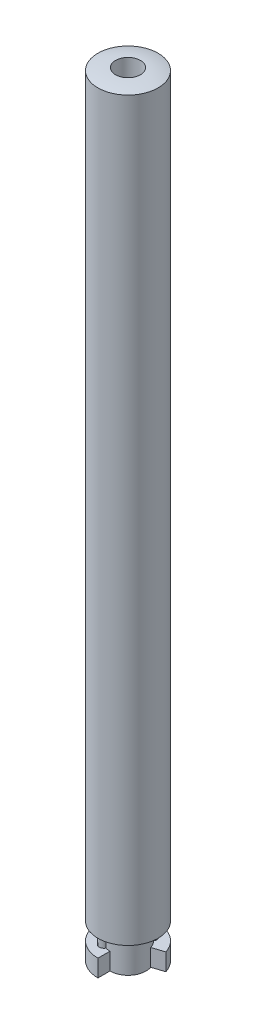
SolidWorks part; units mm, degrees
ref_plane "前视基准面" through (0, 0, 0) normal (0, 0, 1) x (1, 0, 0)
ref_plane "上视基准面" through (0, 0, 0) normal (0, 1, 0) x (1, 0, 0)
ref_plane "右视基准面" through (0, 0, 0) normal (1, 0, 0) x (0, 0, -1)
sketch "草图1" plane through (0, 0, 0) normal (0, 1, 0) x (1, 0, 0)
  circle A0 centre (0, 0) radius 3.5
  dimension "D1" = 7
extrude "凸台-拉伸1" add sketch "草图1" along normal blind 90
sketch "草图2" plane through (0, 0, 0) normal (0, -1, 0) x (1, 0, 0)
  line L0 (0, 0) -> (0, 3.5)
  line L1 (0, 0) -> (3.3287, -1.0816)
  line L2 (0, 3.5) -> (0, 2.1)
  line L3 (0, 0) -> (-3.3287, 1.0816)
  line L4 (0, 0) -> (0, -3.5)
  circle A0 centre (0, 0) radius 3.5 construction
  arc A1 (0, 3.5) -> (3.3287, -1.0816) centre (0, 0) cw
  arc A2 (1.9972, -0.6489) -> (0, 2.1) centre (0, 0) ccw
  arc A3 (0, -3.5) -> (-3.3287, 1.0816) centre (0, 0) cw
  arc A4 (-1.9972, 0.6489) -> (0, -2.1) centre (0, 0) ccw
  point P16 (0, 0)
  circle M1 centre (0, 0) radius 3.5
  dimension "D1" = 108
  dimension "D2" = 1.4
  dimension "D3" = 2
extrude "切除-拉伸1" cut sketch "草图2" against normal blind 2 contours A2 L1 L0 M1 | A4 L3 L4 M1
sketch "草图3" plane through (0, 2, 0) normal (0, -1, 0) x (1, 0, 0)
  circle A0 centre (0, 0) radius 3.5
  circle A1 centre (0, 0) radius 2.1
extrude "切除-拉伸3" cut sketch "草图3" against normal blind 2
sketch "草图4" plane through (0, 2, 0) normal (0, 1, 0) x (1, 0, 0)
  line L0 (-0.5435, -2.0284) -> (-0.9059, -3.3807) construction
  line L2 (0, -3.5) -> (0, -2.1)
  line L3 (-1.9972, -0.6489) -> (-3.3287, -1.0816)
  line L4 (0, -3.5) -> (0, -2.1)
  line L5 (-1.9972, -0.6489) -> (-3.3287, -1.0816)
  circle A0 centre (-0.5435, -2.0284) radius 0.5482 construction
  circle A1 centre (-1.026, -1.7681) radius 0.5482
  arc A2 (-3.3287, -1.0816) -> (0, -3.5) centre (0, 0) ccw
  arc A3 (-1.9972, -0.6489) -> (0, -2.1) centre (0, 0) ccw
  arc A4 (-3.3287, -1.0816) -> (0, -3.5) centre (0, 0) ccw
  arc A5 (-1.9972, -0.6489) -> (0, -2.1) centre (0, 0) ccw
  circle A7 centre (1.026, 1.7681) radius 0.5482
  point P16 (0, 0)
  point P18 (0, 0)
  dimension "D3" = 2
  dimension "D2" = 15
  dimension "D1" = 0
extrude "凸台-拉伸2" add sketch "草图4" along normal blind 2
sketch "草图5" plane through (0, 90, 0) normal (0, 1, 0) x (1, 0, 0)
  circle A0 centre (0, 0) radius 1.45
  dimension "D1" = 2.9
extrude "切除-拉伸5" cut sketch "草图5" against normal blind 10
sketch "草图6" plane through (0, 0, 0) normal (0, 0, 1) x (1, 0, 0)
  line L0 (0, 107.6289) -> (0, 102.8466) construction
  line L2 (3.5, 90) -> (3.5, 89.7)
  line L3 (3.5, 4) -> (3.5, 90) construction
  line L4 (1.3954, 90) -> (1.395, 89.9993)
  line L5 (3.5, 90) -> (1.3954, 90)
  spline S0 degree 3 poles (3.5, 89.7) (2.8106, 89.8888) (2.1089, 89.9886) (1.395, 89.9993) knots 0 0 0 0 0.917895 0.917895 0.917895 0.917895
  dimension "D1" = 0.3
revolve "切除-旋转2" cut sketch "草图6" angle 360 about L0
